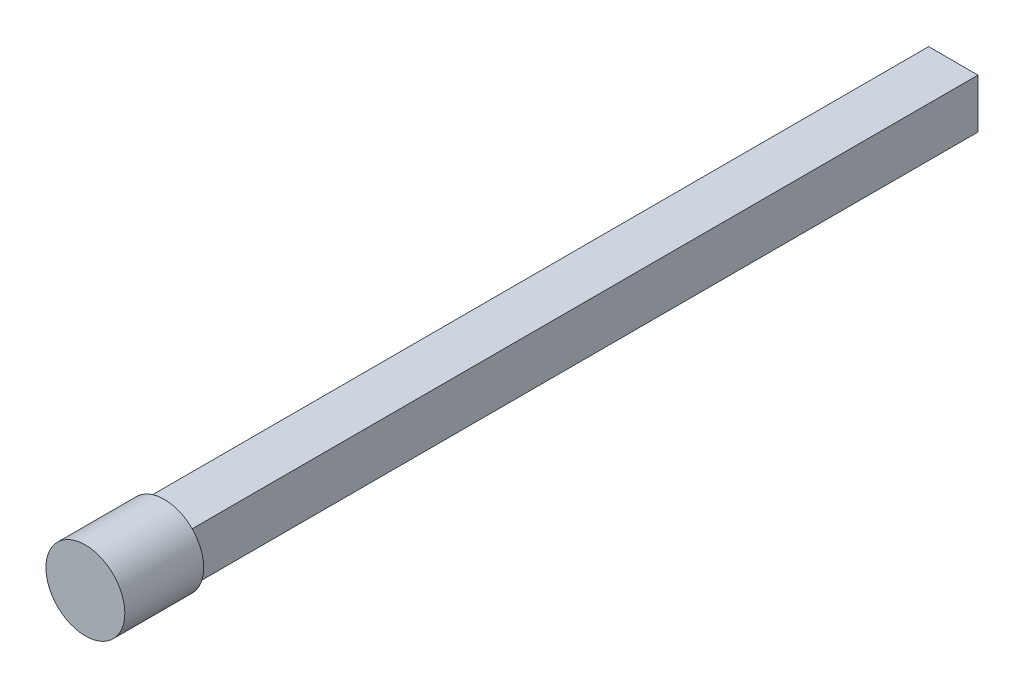
SolidWorks part; units mm, degrees
ref_plane "Front Plane" through (0, 0, 0) normal (0, 0, 1) x (1, 0, 0)
ref_plane "Top Plane" through (0, 0, 0) normal (0, 1, 0) x (1, 0, 0)
ref_plane "Right Plane" through (0, 0, 0) normal (1, 0, 0) x (0, 0, -1)
sketch "Sketch2" plane through (0, 0, 0) normal (0, 0, 1) x (1, 0, 0)
  line L2 (2.5, -2.5) -> (0, -2.5)
  line L3 (2.5, -2.5) -> (2.5, 0)
  line L4 (2.5, 0) -> (0, 0)
  line L5 (0, -2.5) -> (0, 0)
  dimension "D1" = 2.5
extrude "Boss-Extrude1" add sketch "Sketch2" along normal blind 40
sketch "Sketch3" plane through (0, 0, 40) normal (0, 0, 1) x (1, 0, 0)
  line L0 (0, 0) -> (2.5, -2.5) construction
  circle A0 centre (1.25, -1.25) radius 2
  point P2 (1.25, -1.25)
  dimension "D1" = 4
extrude "Boss-Extrude2" add sketch "Sketch3" along normal blind 4
